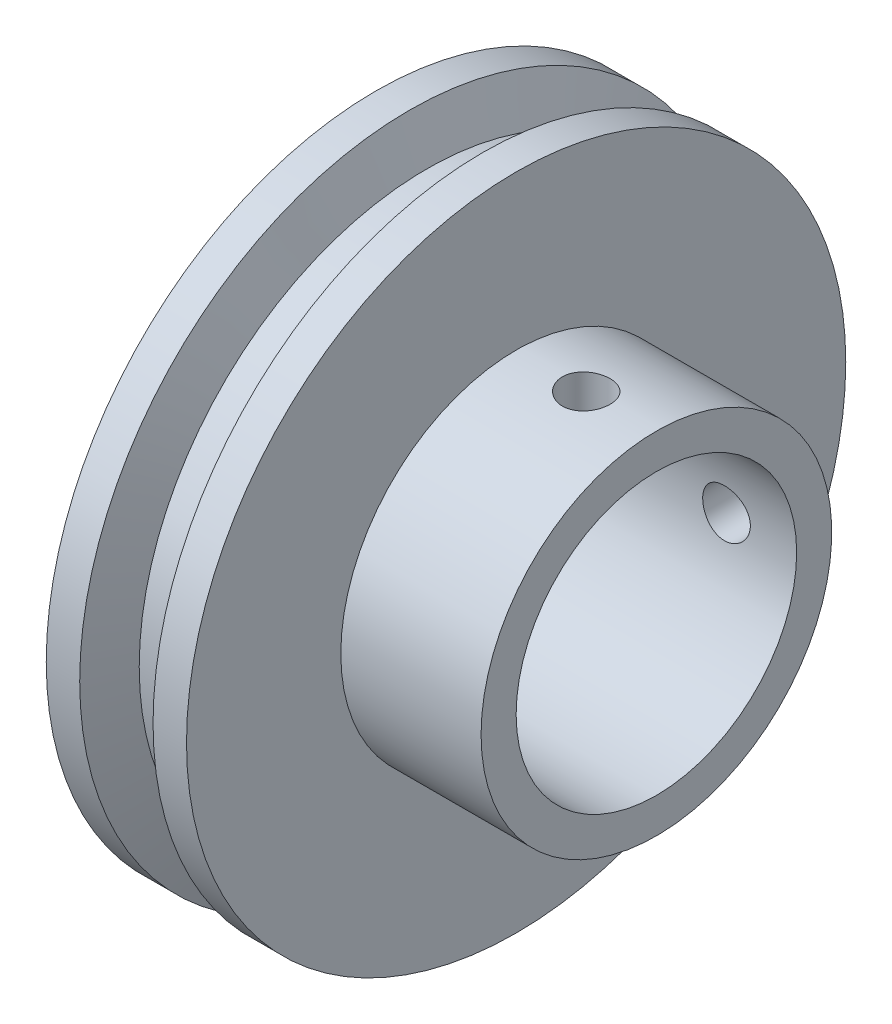
SolidWorks part; units mm, degrees
ref_plane "前视基准面" through (0, 0, 0) normal (0, 0, 1) x (1, 0, 0)
ref_plane "上视基准面" through (0, 0, 0) normal (0, 1, 0) x (1, 0, 0)
ref_plane "右视基准面" through (0, 0, 0) normal (1, 0, 0) x (0, 0, -1)
sketch "草图1" plane through (0, 0, 0) normal (0, 0, 1) x (1, 0, 0)
  line L0 (-5, 0) -> (15, 0) construction
  line L1 (0, 23.5) -> (0, -23.5) construction
  line L2 (0, 20.5) -> (1.3716, 20.5)
  line L3 (1.3716, 20.5) -> (2.6142, 23.5)
  line L4 (2.6142, 23.5) -> (5, 23.5)
  line L5 (5, 23.5) -> (5, 12.5)
  line L6 (5, 12.5) -> (15, 12.5)
  line L7 (15, 12.5) -> (15, 10)
  line L8 (15, 10) -> (0, 10)
  line L9 (-2.2, 22.5) -> (2.2, 22.5) construction
  line L10 (-5, 0) -> (-5, 23.5) construction
  line L11 (10, 12.5) -> (10, 10) construction
  point P18 (12, 12.5)
  dimension "D1" = 47
  dimension "T" = 10
  dimension "D2" = 41
  dimension "PD" = 45
  dimension "D3" = 22.5
  dimension "(d)" = 20
  dimension "L" = 20
  dimension "e" = 5
  dimension "M" = 4
  dimension "D" = 25
  dimension "W" = 4.4
sketch "草图2" plane through (0, 0, 0) normal (1, 0, 0) x (0, 0, -1)
  line L0 (-1.5, 9.8869) -> (-1.5, 11.4)
  line L1 (-1.5, 11.4) -> (1.5, 11.4)
  line L2 (1.5, 11.4) -> (1.5, 9.8869)
  line L3 (0, 0) -> (0, 10) construction
  line L4 (0, 0) -> (0, 23.5) construction
  circle A0 centre (0, 0) radius 10
  dimension "b" = 3
  dimension "t" = 1.4
sketch "草图3" [suppressed] plane through (0, 0, 0) normal (0, 0, 1) x (1, 0, 0)
  line L0 (5, 11) -> (5, 8) construction
  line L1 (2.0642, 11) -> (5, 11) construction
  line L2 (1.0287, 8.5) -> (2.0642, 11) construction
  line L3 (0, 8.5) -> (1.0287, 8.5) construction
  line L4 (5, 11) -> (5, 2)
  line L5 (2.0642, 11) -> (5, 11)
  line L6 (1.0287, 8.5) -> (2.0642, 11)
  line L7 (-1.0287, 8.5) -> (1.0287, 8.5)
  line L8 (11, 2) -> (0, 2) construction
  line L9 (5, 2) -> (-5, 2)
  line L10 (0, 11) -> (0, 0) construction
  line L11 (-1.0287, 8.5) -> (-2.0642, 11)
  line L12 (-2.0642, 11) -> (-5, 11)
  line L13 (-5, 11) -> (-5, 2)
revolve "旋转1" [suppressed] add sketch "草图3" angle 360 about L0
sketch "草图4" [suppressed] plane through (0, 0, 0) normal (0, 0, 1) x (1, 0, 0)
  line L0 (1.275, 0) -> (1.275, 8)
  line L2 (1.275, 8) -> (1.7, 8)
  line L3 (1.7, 8) -> (1.7, 11)
  line L4 (1.7, 11) -> (0, 11)
  line L5 (0, 11) -> (0, 0)
  line L6 (0, 0) -> (1.275, 0)
  line L7 (11, 2) -> (0, 2) construction
  dimension "D1" = 1.275
  dimension "D2" = 1.7
  dimension "D3" = 6
revolve "切除-旋转2" [suppressed] cut sketch "草图4" angle 360 about L1
cosmetic thread "装饰螺纹线1" [suppressed] parameters "D2"=3
pattern_circular "阵列(圆周)1" [suppressed] count 2 every 90
sketch "草图5" [suppressed] plane through (0, 0, 0) normal (1, 0, 0) x (0, 0, -1)
  line L0 (-1.5, 1.3229) -> (-1.5, 3.4) construction
  line L1 (-1.5, 3.4) -> (1.5, 3.4) construction
  line L2 (1.5, 3.4) -> (1.5, 1.3229) construction
  line L3 (-1.5, 1.3229) -> (-1.5, 3.4)
  line L4 (-1.5, 3.4) -> (1.5, 3.4)
  line L5 (1.5, 3.4) -> (1.5, 1.3229)
  circle A0 centre (0, 0) radius 2 construction
  arc A1 (1.5, 1.3229) -> (-1.5, 1.3229) centre (0, 0) ccw
extrude "切除-拉伸1" [suppressed] cut sketch "草图5" against normal through all and the other way through all
sketch "草图6" plane through (0, 0, 0) normal (0, 0, 1) x (1, 0, 0)
  line L0 (15, 12.5) -> (15, 10) construction
  line L1 (5, 12.5) -> (15, 12.5) construction
  line L2 (5, 23.5) -> (5, 12.5) construction
  line L3 (2.6142, 23.5) -> (5, 23.5) construction
  line L4 (1.3716, 20.5) -> (2.6142, 23.5) construction
  line L5 (0, 20.5) -> (1.3716, 20.5) construction
  line L7 (15, 12.5) -> (15, 10)
  line L8 (5, 12.5) -> (15, 12.5)
  line L9 (5, 23.5) -> (5, 12.5)
  line L10 (2.6142, 23.5) -> (5, 23.5)
  line L11 (1.3716, 20.5) -> (2.6142, 23.5)
  line L12 (-1.3716, 20.5) -> (1.3716, 20.5)
  line L13 (15, 10) -> (-5, 10)
  line L14 (0, 0) -> (0, 23.5) construction
  line L15 (-1.3716, 20.5) -> (-2.6142, 23.5)
  line L16 (-2.6142, 23.5) -> (-5, 23.5)
  line L17 (-5, 23.5) -> (-5, 10)
  line L19 (-5, 0) -> (-5, 23.5) construction
revolve "旋转2" add sketch "草图6" angle 360 about L0
sketch "草图7" plane through (0, 0, 0) normal (0, 0, 1) x (1, 0, 0)
  line L0 (10, 23.5) -> (10, 0)
  line L1 (10, 0) -> (11.7, 0)
  line L2 (11.7, 0) -> (11.7, 23.5)
  line L3 (11.7, 23.5) -> (10, 23.5)
  line L4 (-5, 0) -> (15, 0) construction
  dimension "D1" = 1.7
revolve "切除-旋转3" cut sketch "草图7" angle 360 about L0
cosmetic thread "装饰螺纹线2" parameters "D2"=4
pattern_circular "阵列(圆周)2" count 2 every 90 about axis through (-5, 0, 0) along (-1, 0, 0) of "切除-旋转3"
sketch "草图8" [suppressed] plane through (0, 0, 0) normal (1, 0, 0) x (0, 0, -1)
  line L0 (-1.5, 1.3229) -> (-1.5, 3.4) construction
  line L1 (-1.5, 3.4) -> (1.5, 3.4) construction
  line L2 (1.5, 3.4) -> (1.5, 1.3229) construction
  line L3 (-1.5, 1.3229) -> (-1.5, 3.4)
  line L4 (-1.5, 3.4) -> (1.5, 3.4)
  line L5 (1.5, 3.4) -> (1.5, 1.3229)
  circle A0 centre (0, 0) radius 2 construction
  arc A1 (1.5, 1.3229) -> (-1.5, 1.3229) centre (0, 0) ccw
extrude "切除-拉伸2" [suppressed] cut sketch "草图8" against normal through all and the other way through all
sketch "草图9" [suppressed] plane through (0, 0, 0) normal (0, 0, 1) x (1, 0, 0)
  line L1 (2.0642, 11) -> (5, 11) construction
  line L2 (5, 11) -> (5, 2)
  line L3 (2.3094, 11) -> (5, 11)
  line L4 (0, 11) -> (0, -11) construction
  line L5 (-1.65, 10) -> (1.65, 10) construction
  line L6 (1.299, 9.25) -> (2.3094, 11)
  line L7 (0, 11) -> (0, 0) construction
  line L8 (11, 2) -> (0, 2) construction
  line L9 (-2.3094, 11) -> (-5, 11)
  line L10 (-1.299, 9.25) -> (-2.3094, 11)
  line L11 (5, 2) -> (-5, 2)
  line L12 (-5, 0) -> (-5, 11) construction
  line L13 (-5, 2) -> (-5, 11)
  arc A0 (-1.299, 9.25) -> (1.299, 9.25) centre (0, 10) ccw
  dimension "D1" = 30
revolve "旋转3" [suppressed] add sketch "草图9" angle 360 about L0
sketch "草图10" [suppressed] plane through (0, 0, 0) normal (0, 0, 1) x (1, 0, 0)
  line L0 (1.7, 11) -> (1.7, 8)
  line L1 (1.7, 8) -> (1.275, 8)
  line L2 (1.275, 8) -> (1.275, 0)
  line L3 (-5, 0) -> (11, 0) construction
  line L4 (1.275, 0) -> (0, 0)
  line L5 (0, 0) -> (0, 11)
  line L6 (0, 11) -> (1.7, 11)
  line L7 (11, 2) -> (0, 2) construction
  dimension "D1" = 1.275
  dimension "D2" = 1.7
  dimension "D3" = 6
revolve "切除-旋转4" [suppressed] cut sketch "草图10" angle 360 about L1
cosmetic thread "装饰螺纹线3" [suppressed] parameters "D2"=3
pattern_circular "阵列(圆周)3" [suppressed] count 2 every 90
sketch "草图11" [suppressed] plane through (0, 0, 0) normal (1, 0, 0) x (0, 0, -1)
  line L0 (-1.5, 1.3229) -> (-1.5, 3.4) construction
  line L1 (-1.5, 3.4) -> (1.5, 3.4) construction
  line L2 (1.5, 3.4) -> (1.5, 1.3229) construction
  line L3 (-1.5, 1.3229) -> (-1.5, 3.4)
  line L4 (-1.5, 3.4) -> (1.5, 3.4)
  line L5 (1.5, 3.4) -> (1.5, 1.3229)
  circle A0 centre (0, 0) radius 2 construction
  arc A1 (1.5, 1.3229) -> (-1.5, 1.3229) centre (0, 0) ccw
extrude "切除-拉伸3" [suppressed] cut sketch "草图11" against normal through all and the other way through all
sketch "草图12" [suppressed] plane through (0, 0, 0) normal (0, 0, 1) x (1, 0, 0)
  line L0 (2.0642, 11) -> (5, 11) construction
  line L1 (2.3094, 11) -> (5, 11)
  line L2 (-1.65, 10) -> (1.65, 10) construction
  line L3 (1.299, 9.25) -> (2.3094, 11)
  line L4 (0, 11) -> (0, -11) construction
  line L5 (0, 11) -> (0, 0) construction
  line L6 (-2.3094, 11) -> (-5, 11)
  line L7 (-1.299, 9.25) -> (-2.3094, 11)
  line L8 (5, 11) -> (5, 8)
  line L9 (5, 8) -> (11, 8)
  line L10 (11, 8) -> (11, 2)
  line L11 (11, 2) -> (-5, 2)
  line L12 (-5, 0) -> (-5, 11) construction
  line L13 (-5, 2) -> (-5, 11)
  arc A0 (-1.299, 9.25) -> (1.299, 9.25) centre (0, 10) ccw
  dimension "D1" = 30
revolve "旋转4" [suppressed] add sketch "草图12" angle 360 about L0
sketch "草图13" [suppressed] plane through (0, 0, 0) normal (0, 0, 1) x (1, 0, 0)
  line L0 (8, 11) -> (8, 0)
  line L1 (-5, 0) -> (11, 0) construction
  line L2 (8, 0) -> (9.275, 0)
  line L4 (9.275, 0) -> (9.275, 11)
  line L5 (9.275, 11) -> (8, 11)
  dimension "D1" = 1.7
revolve "切除-旋转5" [suppressed] cut sketch "草图13" angle 360 about L0
cosmetic thread "装饰螺纹线4" [suppressed] parameters "D2"=4
pattern_circular "阵列(圆周)4" [suppressed] count 2 every 90
sketch "草图14" [suppressed] plane through (0, 0, 0) normal (1, 0, 0) x (0, 0, -1)
  line L0 (-1.5, 1.3229) -> (-1.5, 3.4) construction
  line L1 (-1.5, 3.4) -> (1.5, 3.4) construction
  line L2 (1.5, 3.4) -> (1.5, 1.3229) construction
  line L3 (-1.5, 1.3229) -> (-1.5, 3.4)
  line L4 (-1.5, 3.4) -> (1.5, 3.4)
  line L5 (1.5, 3.4) -> (1.5, 1.3229)
  circle A0 centre (0, 0) radius 2 construction
  arc A1 (1.5, 1.3229) -> (-1.5, 1.3229) centre (0, 0) ccw
extrude "切除-拉伸4" [suppressed] cut sketch "草图14" against normal through all and the other way through all
